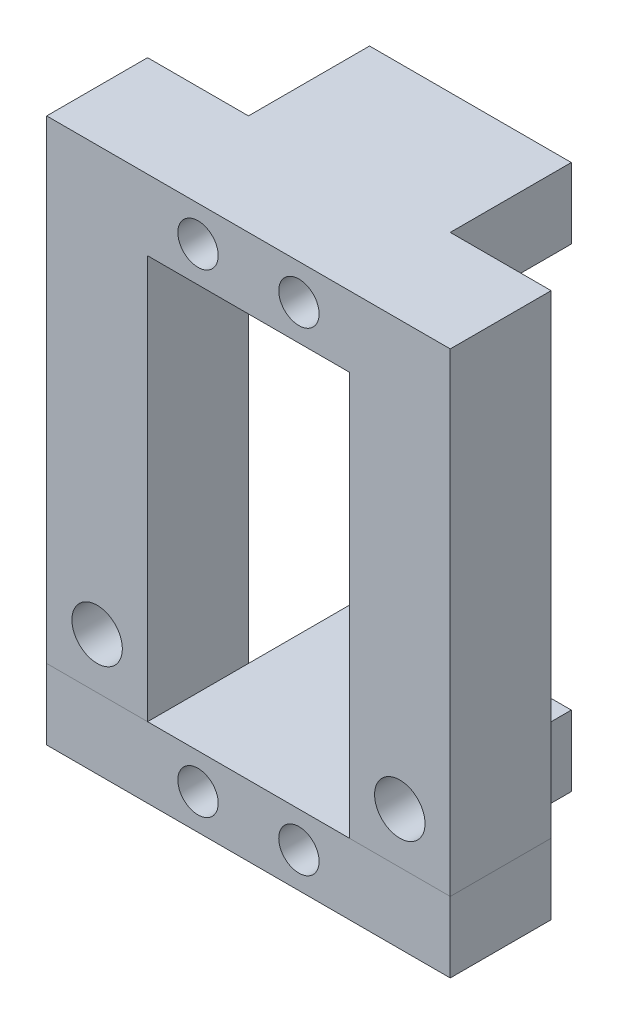
SolidWorks part; units mm, degrees
ref_plane "Front" through (0, 0, 0) normal (0, 0, 1) x (1, 0, 0)
ref_plane "Top" through (0, 0, 0) normal (0, 1, 0) x (1, 0, 0)
ref_plane "Right" through (0, 0, 0) normal (1, 0, 0) x (0, 0, -1)
sketch "Эскиз1" plane through (0, 0, 0) normal (0, 0, 1) x (1, 0, 0)
  line L0 (0, 11.7347) -> (0, -10.4422) construction
  line L1 (-19.9319, 0) -> (18.1632, 0) construction
  line L3 (-20, 5) -> (-10, 5)
  line L4 (-20, 5) -> (-20, -5)
  line L5 (-20, -5) -> (-10, -5)
  line L6 (-10, 5) -> (-10, -5)
  line L7 (-20, 5) -> (-10, -5) construction
  line L8 (-20, -5) -> (-10, 5) construction
  line L9 (10, 5) -> (20, 5)
  line L10 (10, 5) -> (10, -5)
  line L11 (10, -5) -> (20, -5)
  line L12 (20, 5) -> (20, -5)
  line L13 (10, 5) -> (20, -5) construction
  line L14 (10, -5) -> (20, 5) construction
  line L15 (-20, -5) -> (20, -5)
  line L18 (20, -5) -> (20, -12)
  circle A0 centre (-15, 0) radius 2.5
  circle A1 centre (15, 0) radius 2.5
  dimension "D1" = 5
  dimension "D3" = 30
  dimension "D2" = 10
  dimension "D4" = 10
extrude "Бобышка-Вытянуть2" add sketch "Эскиз1" along normal blind 10 contours L6 L3 L4 L5 A0 | L12 L9 L10 L11 A1
sketch "Эскиз2" plane through (0, 0, 0) normal (0, 0, 1) x (1, 0, 0)
  line L1 (-20, -5) -> (20, -5)
  line L2 (-20, -5) -> (-20, -12)
  line L3 (-20, -12) -> (20, -12)
  line L4 (20, -5) -> (20, -12)
  dimension "D1" = 7
extrude "Бобышка-Вытянуть3" add sketch "Эскиз2" along normal blind 10 separate body
sketch "Эскиз3" plane through (0, 0, 0) normal (0, 0, -1) x (-1, 0, 0)
  line L0 (20, -12) -> (-20, -12) construction
  line L1 (-10, -5) -> (10, -5)
  line L2 (-10, -5) -> (-10, -12)
  line L3 (-10, -12) -> (10, -12)
  line L4 (10, -5) -> (10, -12)
  line L5 (10, 5) -> (10, -5) construction
  line L6 (-20, -5) -> (20, -5) construction
extrude "Бобышка-Вытянуть4" add sketch "Эскиз3" along normal blind 12
sketch "Эскиз4" plane through (0, 0, -12) normal (0, 0, -1) x (-1, 0, 0)
  circle A0 centre (-5, -8.5) radius 2
  circle A1 centre (5, -8.5) radius 2
  dimension "D1" = 4
extrude "Вырез-Вытянуть1" cut sketch "Эскиз4" against normal through all
sketch "Эскиз5" plane through (0, 5, 0) normal (0, 1, 0) x (1, 0, 0)
  line L1 (-20, 0) -> (-10, 0)
  line L2 (-20, 0) -> (-20, -10)
  line L3 (-20, -10) -> (-10, -10)
  line L4 (-10, 0) -> (-10, -10)
  line L5 (10, 0) -> (20, 0)
  line L6 (10, 0) -> (10, -10)
  line L7 (10, -10) -> (20, -10)
  line L8 (20, 0) -> (20, -10)
extrude "Бобышка-Вытянуть5" add sketch "Эскиз5" along normal up to surface (30 mm away)
sketch "Эскиз6" plane through (0, 35, 0) normal (0, 1, 0) x (1, 0, 0)
  line L1 (-20, 0) -> (20, 0)
  line L2 (-20, 0) -> (-20, -10)
  line L3 (-20, -10) -> (20, -10)
  line L4 (20, 0) -> (20, -10)
  line L5 (-10, 12) -> (10, 12)
  line L6 (-10, 12) -> (-10, 0)
  line L7 (-10, 0) -> (10, 0)
  line L8 (10, 12) -> (10, 0)
  line M1 (20, 0) -> (10, 0)
  line M2 (10, 0) -> (10, -10)
  line M3 (10, -10) -> (20, -10)
  line M4 (20, -10) -> (20, 0)
extrude "Бобышка-Вытянуть6" add sketch "Эскиз6" along normal blind 7 contours L8 L5 L6 L1 | L2 L3 L1 M2 | M4 M1 M2 M3
sketch "Эскиз7" plane through (0, 0, -12) normal (0, 0, -1) x (-1, 0, 0)
  circle A0 centre (-5, 38.5) radius 2
  circle A1 centre (5, 38.5) radius 2
  dimension "D1" = 4
extrude "Вырез-Вытянуть2" cut sketch "Эскиз7" against normal through all
